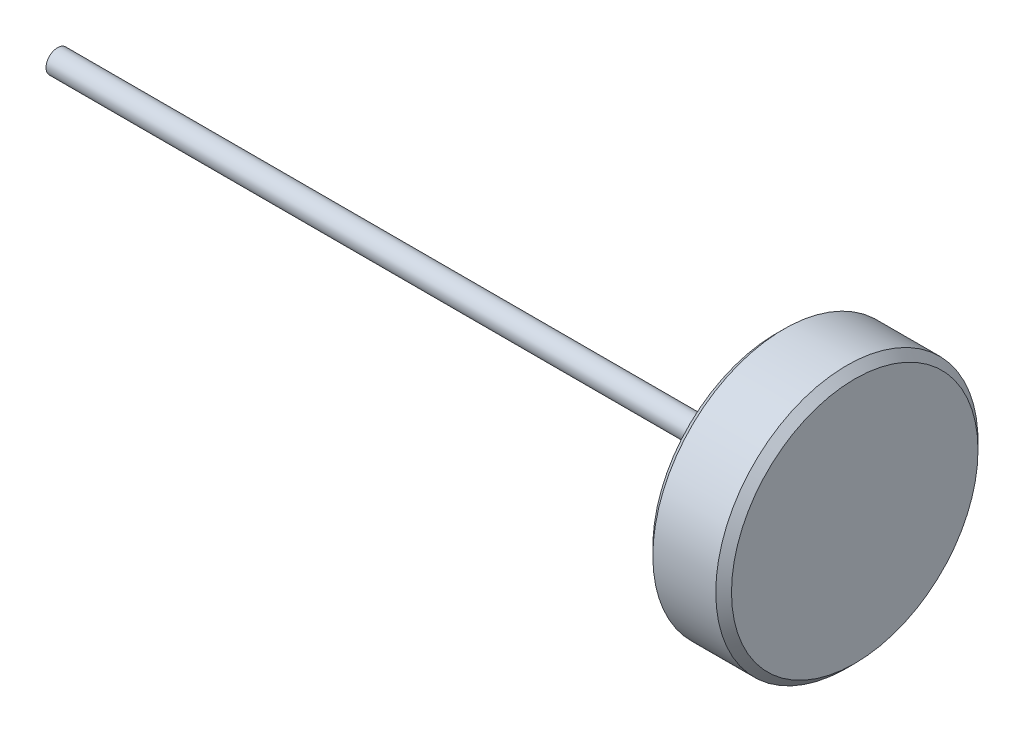
SolidWorks part; units mm, degrees
material "PLA"
ref_plane "Front Plane" through (0, 0, 0) normal (0, 0, 1) x (1, 0, 0)
ref_plane "Top Plane" through (0, 0, 0) normal (0, 1, 0) x (1, 0, 0)
ref_plane "Right Plane" through (0, 0, 0) normal (1, 0, 0) x (0, 0, -1)
sketch "Sketch1" plane through (0, 0, 0) normal (1, 0, 0) x (0, 0, -1)
  circle A0 centre (0, 0) radius 31.75
  dimension "D1" = 63.5
extrude "Boss-Extrude1" add sketch "Sketch1" along normal blind 19.05
sketch "Sketch2" plane through (0, 0, 0) normal (-1, 0, 0) x (0, 0, 1)
  circle A0 centre (0, 0) radius 2.794
  dimension "D1" = 5.588
extrude "Boss-Extrude2" add sketch "Sketch2" along normal blind 173.99
fillet "Fillet1" radius 4.445 1 edges at (0, 0, -2.794)
chamfer "Chamfer1" distance 1.905 angle 45 2 edges at (19.05, 0, -31.75) (0, 0, -31.75)
